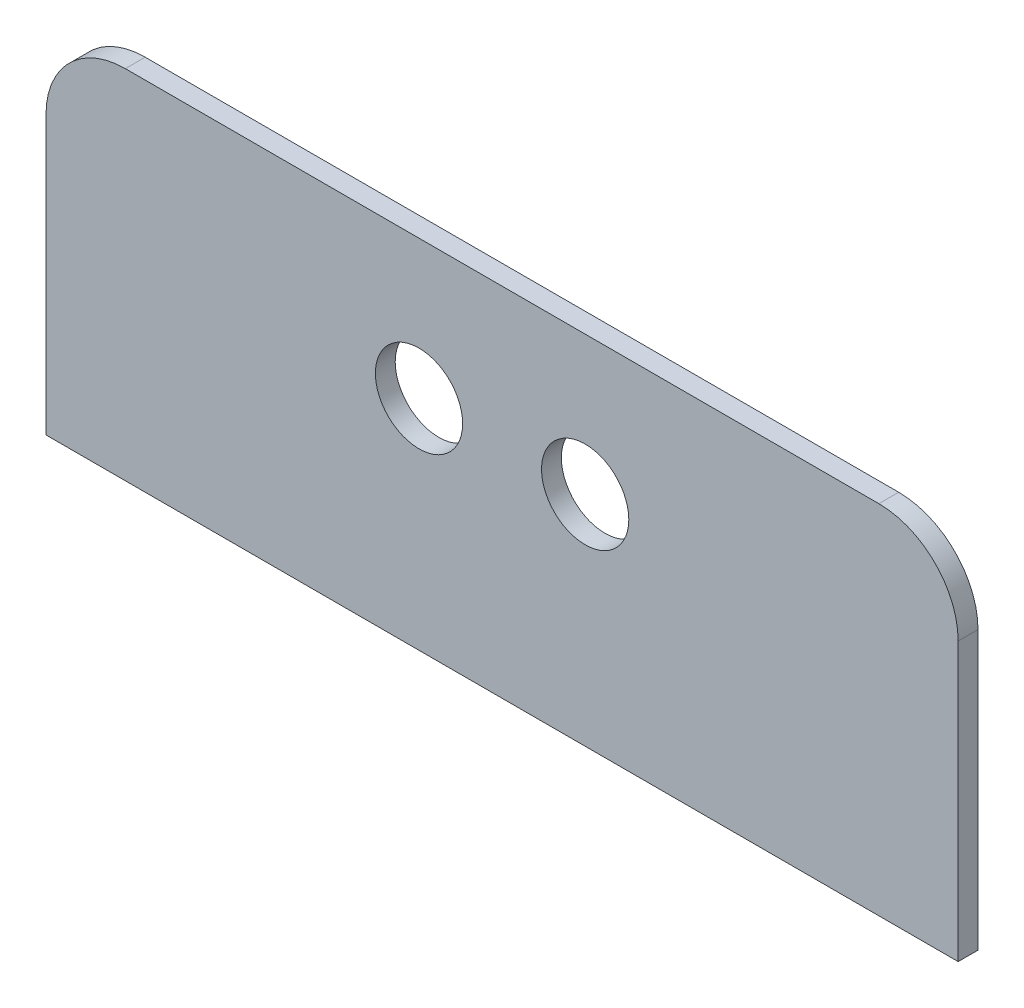
SolidWorks part; units mm, degrees
ref_plane "Front Plane" through (0, 0, 0) normal (0, 0, 1) x (1, 0, 0)
ref_plane "Top Plane" through (0, 0, 0) normal (0, 1, 0) x (1, 0, 0)
ref_plane "Right Plane" through (0, 0, 0) normal (1, 0, 0) x (0, 0, -1)
sketch "Sketch1" plane through (0, 0, 0) normal (0, 0, 1) x (1, 0, 0)
  line L1 (-115, -45) -> (115, -45)
  line L2 (-115, -45) -> (-115, 45)
  line L3 (-115, 45) -> (115, 45)
  line L4 (115, -45) -> (115, 45)
  line L5 (-115, -45) -> (115, 45) construction
  line L6 (-115, 45) -> (115, -45) construction
  point P0 (0, 0)
  dimension "D1" = 230
  dimension "D2" = 90
extrude "Boss-Extrude1" add sketch "Sketch1" along normal blind 5
fillet "Fillet1" radius 20 2 edges at (115, 45, 2.5) (-115, 45, 2.5)
sketch "Sketch2" plane through (0, 0, 5) normal (0, 0, 1) x (1, 0, 0)
  line L0 (-115, 10) -> (115, 10) construction
  line L1 (-115, 25) -> (-115, -45) construction
  line L2 (115, -45) -> (115, 25) construction
  circle A0 centre (-20.95, 10) radius 11
  circle A1 centre (20.95, 10) radius 11
  dimension "D2" = 22
  dimension "D1" = 41.9
  dimension "D3" = 20.95
  dimension "D7" = 10
extrude "Cut-Extrude1" cut sketch "Sketch2" against normal up to next
